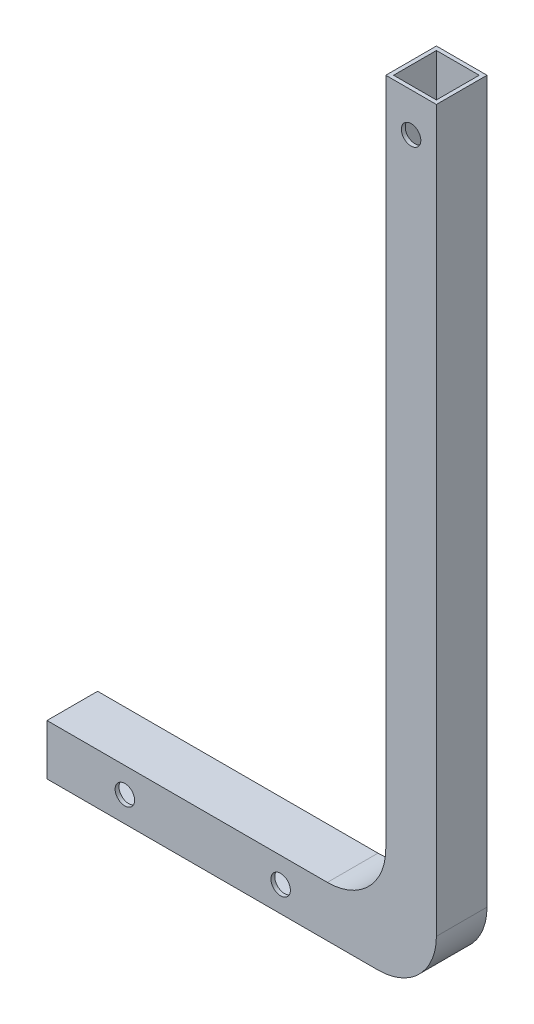
SolidWorks part; units mm, degrees
material "Plain Carbon Steel"
ref_plane "Front Plane" through (0, 0, 0) normal (0, 0, 1) x (1, 0, 0)
ref_plane "Top Plane" through (0, 0, 0) normal (0, 1, 0) x (1, 0, 0)
ref_plane "Right Plane" through (0, 0, 0) normal (1, 0, 0) x (0, 0, -1)
sketch "Sketch1" plane through (0, 0, 0) normal (0, 0, 1) x (1, 0, 0)
  line L0 (0, 0) -> (0, -33.02)
  line L1 (0, -33.02) -> (215.9, -33.02)
  line L2 (254, 5.08) -> (254, 474.98)
  line L3 (254, 474.98) -> (220.98, 474.98)
  line L4 (220.98, 474.98) -> (220.98, 38.1)
  line L5 (182.88, 0) -> (0, 0)
  arc A0 (215.9, -33.02) -> (254, 5.08) centre (215.9, 5.08) ccw
  arc A1 (220.98, 38.1) -> (182.88, 0) centre (182.88, 38.1) cw
  point P9 (254, -33.02)
  dimension "D5" = 38.1
  dimension "D1" = 33.02
  dimension "D2" = 33.02
  dimension "D3" = 254
  dimension "D4" = 508
extrude "Boss-Extrude1" add sketch "Sketch1" along normal blind 33.02
shell "Shell1" thickness 2.54
sketch "Sketch2" plane through (0, 474.98, 0) normal (0, 1, 0) x (1, 0, 0)
  line L8 (251.46, -2.54) -> (223.52, -2.54)
  line L9 (223.52, -2.54) -> (223.52, -30.48)
  line L10 (223.52, -30.48) -> (251.46, -30.48)
  line L11 (251.46, -30.48) -> (251.46, -2.54)
  line L12 (251.46, -2.54) -> (223.52, -2.54)
  line L13 (223.52, -2.54) -> (223.52, -30.48)
  line L14 (223.52, -30.48) -> (251.46, -30.48)
  line L15 (251.46, -30.48) -> (251.46, -2.54)
  dimension "D1" = 2.54
extrude "Cut-Extrude1" cut sketch "Sketch2" against normal up to next
sketch "Sketch3" plane through (0, 0, 33.02) normal (0, 0, 1) x (1, 0, 0)
  line L2 (0, 0) -> (0, -33.02) construction
  line L3 (0, -33.02) -> (215.9, -33.02) construction
  circle A0 centre (50.8, -16.51) radius 6.35
  circle A1 centre (152.4, -16.51) radius 6.35
  dimension "D1" = 12.7
  dimension "D2" = 50.8
  dimension "D3" = 152.4
  dimension "D4" = 16.51
extrude "Cut-Extrude2" cut sketch "Sketch3" against normal through all
sketch "Sketch4" plane through (0, 0, 33.02) normal (0, 0, 1) x (1, 0, 0)
  line L0 (254, 474.98) -> (220.98, 474.98) construction
  line L1 (0, 0) -> (0, -33.02) construction
  circle A0 centre (237.49, 449.58) radius 6.35
  dimension "D1" = 12.7
  dimension "D2" = 25.4
  dimension "D3" = 237.49
extrude "Cut-Extrude3" cut sketch "Sketch4" against normal through all
